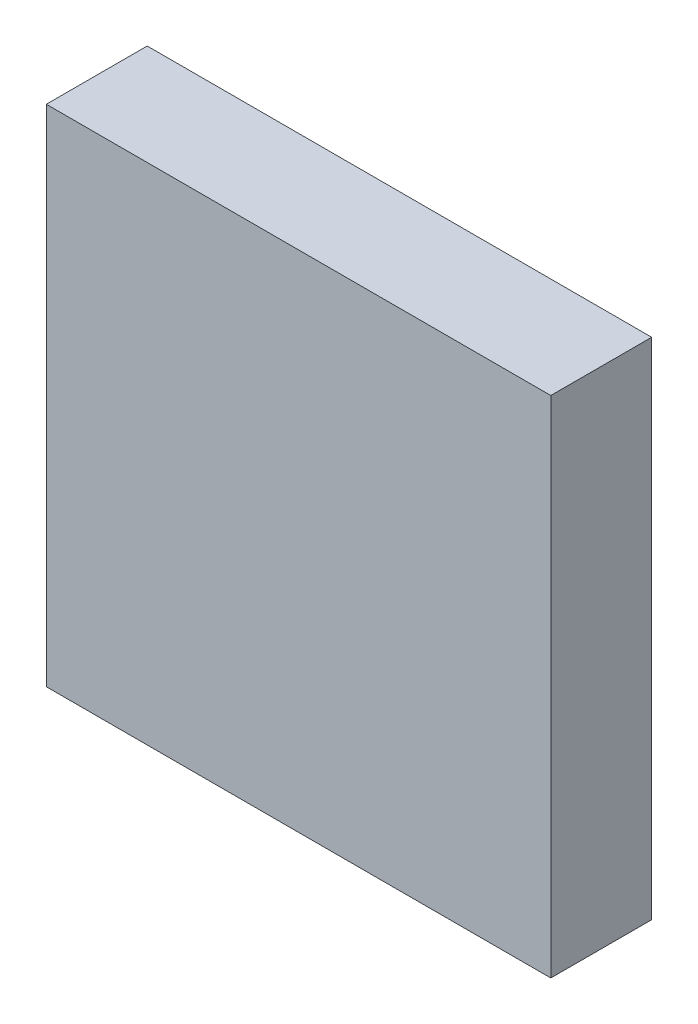
SolidWorks part; units mm, degrees
ref_plane "Спереди" through (0, 0, 0) normal (0, 0, 1) x (1, 0, 0)
ref_plane "Сверху" through (0, 0, 0) normal (0, 1, 0) x (1, 0, 0)
ref_plane "Справа" through (0, 0, 0) normal (1, 0, 0) x (0, 0, -1)
sketch "Эскиз1" plane through (0, 0, 0) normal (0, 0, 1) x (1, 0, 0)
  line L1 (0, 0) -> (20, 0)
  line L2 (0, 0) -> (0, 20)
  line L3 (0, 20) -> (20, 20)
  line L4 (20, 0) -> (20, 20)
  dimension "D1" = 20
  dimension "D2" = 20
extrude "Бобышка-Вытянуть1" add sketch "Эскиз1" along normal blind 4
